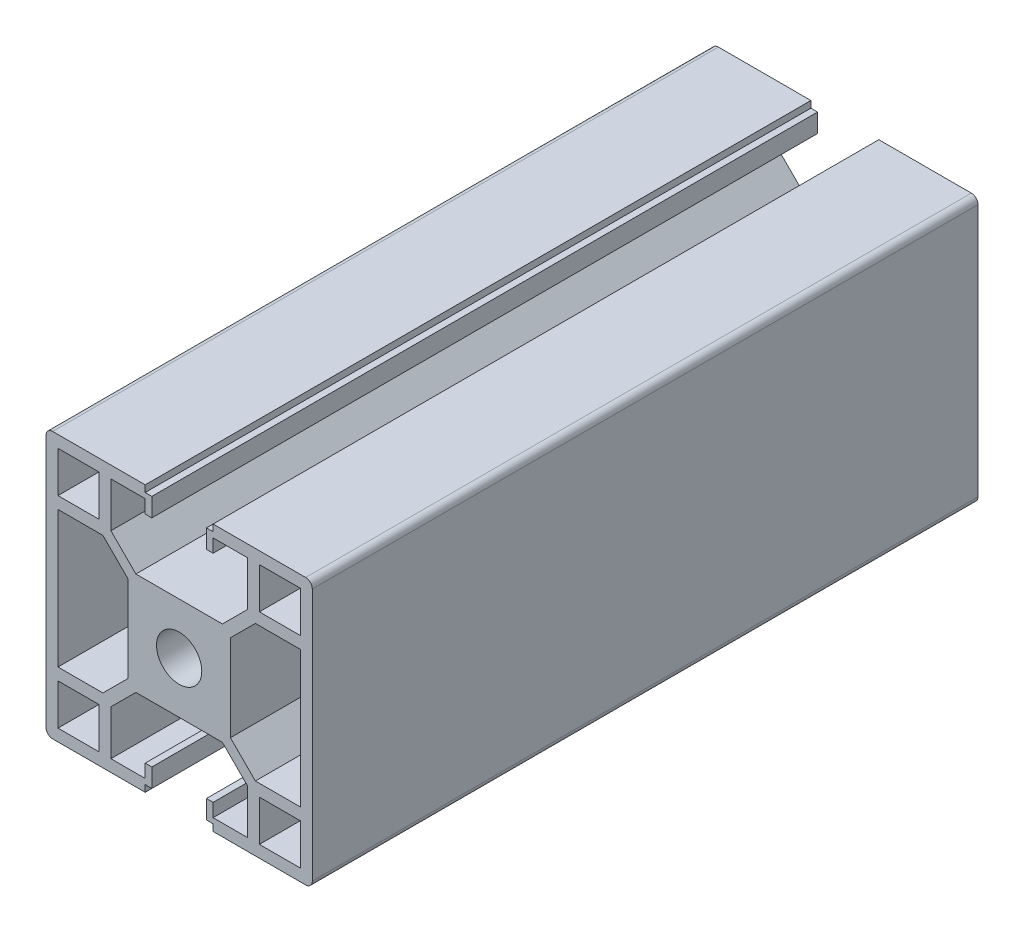
SolidWorks part; units mm, degrees
ref_plane "前视基准面" through (0, 0, 0) normal (0, 0, 1) x (1, 0, 0)
ref_plane "上视基准面" through (0, 0, 0) normal (0, 1, 0) x (1, 0, 0)
ref_plane "右视基准面" through (0, 0, 0) normal (1, 0, 0) x (0, 0, -1)
sketch "草图1" plane through (0, 0, 0) normal (0, 0, 1) x (1, 0, 0)
  line L0 (-4.0688, 19.5458) -> (-17.9688, 19.5458)
  line L2 (-3.0688, 15.7458) -> (-4.0688, 15.7458)
  line L3 (-4.0688, 17.7458) -> (-9.2188, 17.7458)
  line L4 (-11.0188, 17.7458) -> (-17.1688, 17.7458)
  line L5 (-17.1688, 17.7458) -> (-17.1688, 11.5958)
  line L7 (-3.0688, 18.5458) -> (-4.0688, 18.5458)
  line L8 (-6.6688, 6.0437) -> (-6.6688, -6.9521)
  line L9 (-5.4667, -8.1542) -> (7.5291, -8.1542)
  line L10 (8.7312, -6.9521) -> (8.7312, 6.0437)
  line L11 (7.5291, 7.2458) -> (-5.4667, 7.2458)
  line L12 (-17.1688, 9.7958) -> (-10.4209, 9.7958)
  line L13 (-17.1688, 11.5958) -> (-11.0188, 11.5958)
  line L14 (-9.2188, 17.7458) -> (-9.2188, 10.9979)
  line L15 (-11.0188, 17.7458) -> (-11.0188, 11.5958)
  line L16 (-4.0688, 19.5458) -> (-4.0688, 18.5458)
  line L17 (-4.0688, 17.7458) -> (-4.0688, 15.7458)
  line L18 (-3.0688, 18.5458) -> (-3.0688, 15.7458)
  line L19 (-9.2188, 10.9979) -> (-5.4667, 7.2458)
  line L20 (-10.4209, 9.7958) -> (-6.6688, 6.0437)
  line L21 (6.1312, 19.5458) -> (20.0312, 19.5458)
  line L23 (5.1312, 15.7458) -> (6.1312, 15.7458)
  line L25 (6.1312, 17.7458) -> (11.2812, 17.7458)
  line L26 (13.0812, 17.7458) -> (19.2312, 17.7458)
  line L27 (19.2312, 17.7458) -> (19.2312, 11.5958)
  line L30 (5.1312, 18.5458) -> (6.1312, 18.5458)
  line L31 (19.2312, 9.7958) -> (12.4833, 9.7958)
  line L32 (19.2312, 11.5958) -> (13.0812, 11.5958)
  line L36 (11.2812, 17.7458) -> (11.2812, 10.9979)
  line L37 (13.0812, 17.7458) -> (13.0812, 11.5958)
  line L38 (6.1312, 19.5458) -> (6.1312, 18.5458)
  line L39 (6.1312, 17.7458) -> (6.1312, 15.7458)
  line L40 (5.1312, 18.5458) -> (5.1312, 15.7458)
  line L41 (11.2812, 10.9979) -> (7.5291, 7.2458)
  line L42 (12.4833, 9.7958) -> (8.7312, 6.0437)
  line L44 (-18.9688, -19.4542) -> (-18.9688, 18.5458)
  line L46 (-11.0188, -18.6542) -> (-17.1688, -18.6542)
  line L47 (-17.1688, -18.6542) -> (-17.1688, -12.5042)
  line L48 (-17.1688, -10.7042) -> (-17.1688, 9.7958)
  line L49 (-17.1688, -10.7042) -> (-10.4209, -10.7042)
  line L50 (-17.1688, -12.5042) -> (-11.0188, -12.5042)
  line L51 (-9.2188, -18.6542) -> (-9.2188, -11.9063)
  line L52 (-11.0188, -18.6542) -> (-11.0188, -12.5042)
  line L53 (-9.2188, -11.9063) -> (-5.4667, -8.1542)
  line L54 (-10.4209, -10.7042) -> (-6.6688, -6.9521)
  line L55 (-17.9688, -20.4542) -> (-4.0688, -20.4542)
  line L56 (21.0312, -19.4542) -> (21.0312, 18.5458)
  line L58 (-9.2188, -18.6542) -> (-4.0688, -18.6542)
  line L59 (13.0812, -18.6542) -> (19.2312, -18.6542)
  line L60 (19.2312, -18.6542) -> (19.2312, -12.5042)
  line L61 (19.2312, -10.7042) -> (19.2312, 9.7958)
  line L63 (19.2312, -10.7042) -> (12.4833, -10.7042)
  line L64 (19.2312, -12.5042) -> (13.0812, -12.5042)
  line L65 (5.1312, -16.6542) -> (6.1312, -16.6542)
  line L66 (5.1312, -19.4542) -> (6.1312, -19.4542)
  line L67 (11.2812, -18.6542) -> (11.2812, -11.9063)
  line L68 (13.0812, -18.6542) -> (13.0812, -12.5042)
  line L69 (11.2812, -11.9063) -> (7.5291, -8.1542)
  line L70 (12.4833, -10.7042) -> (8.7312, -6.9521)
  line L71 (6.1312, -20.4542) -> (6.1312, -19.4542)
  line L73 (6.1312, -18.6542) -> (6.1312, -16.6542)
  line L74 (5.1312, -19.4542) -> (5.1312, -16.6542)
  line L75 (-3.0688, -16.6542) -> (-4.0688, -16.6542)
  line L76 (-3.0688, -19.4542) -> (-4.0688, -19.4542)
  line L77 (-4.0688, -20.4542) -> (-4.0688, -19.4542)
  line L78 (-4.0688, -18.6542) -> (-4.0688, -16.6542)
  line L79 (-3.0688, -19.4542) -> (-3.0688, -16.6542)
  line L90 (1.0312, -0.4542) -> (5.1312, 15.7458) construction
  line L91 (1.0312, -0.4542) -> (17.2312, -4.5542) construction
  line L92 (6.1312, -20.4542) -> (20.0312, -20.4542)
  line L93 (6.1312, -18.6542) -> (11.2812, -18.6542)
  line L94 (-15.1688, -4.5542) -> (-15.1688, -5.5542) [skipped]
  line L95 (-17.9688, -4.5542) -> (-17.9688, -5.5542) [skipped]
  line L96 (-18.9688, -5.5542) -> (-17.9688, -5.5542) [skipped]
  line L97 (-17.1688, -5.5542) -> (-15.1688, -5.5542) [skipped]
  line L98 (-17.9688, -4.5542) -> (-15.1688, -4.5542) [skipped]
  line L99 (-15.1688, 3.6458) -> (-15.1688, 4.6458) [skipped]
  line L100 (-17.9688, 3.6458) -> (-17.9688, 4.6458) [skipped]
  line L101 (-18.9688, 4.6458) -> (-17.9688, 4.6458) [skipped]
  line L102 (-17.1688, 4.6458) -> (-15.1688, 4.6458) [skipped]
  line L103 (-17.9688, 3.6458) -> (-15.1688, 3.6458) [skipped]
  line L104 (17.2312, 3.6458) -> (17.2312, 4.6458) [skipped]
  line L105 (20.0312, 3.6458) -> (20.0312, 4.6458) [skipped]
  line L106 (21.0312, 4.6458) -> (20.0312, 4.6458) [skipped]
  line L107 (19.2312, 4.6458) -> (17.2312, 4.6458) [skipped]
  line L108 (20.0312, 3.6458) -> (17.2312, 3.6458) [skipped]
  line L109 (17.2312, -4.5542) -> (17.2312, -5.5542) [skipped]
  line L110 (20.0312, -4.5542) -> (20.0312, -5.5542) [skipped]
  line L111 (21.0312, -5.5542) -> (20.0312, -5.5542) [skipped]
  line L112 (19.2312, -5.5542) -> (17.2312, -5.5542) [skipped]
  line L113 (20.0312, -4.5542) -> (17.2312, -4.5542) [skipped]
  arc A0 (-17.9688, 19.5458) -> (-18.9688, 18.5458) centre (-17.9688, 18.5458) ccw
  arc A1 (21.0312, 18.5458) -> (20.0312, 19.5458) centre (20.0312, 18.5458) ccw
  arc A2 (-18.9688, -19.4542) -> (-17.9688, -20.4542) centre (-17.9688, -19.4542) ccw
  arc A3 (20.0312, -20.4542) -> (21.0312, -19.4542) centre (20.0312, -19.4542) ccw
  circle A4 centre (1.0312, -0.4542) radius 3.4
  dimension "D2" = 90
  dimension "D1" = 4
extrude "凸台-拉伸1" add sketch "草图1" along normal blind 100
